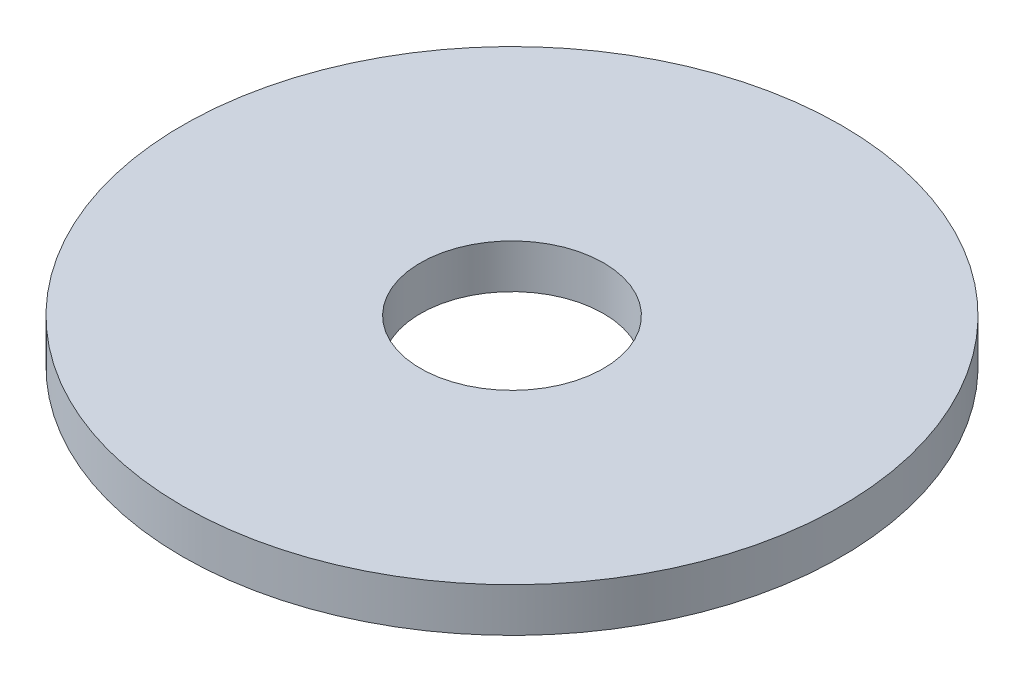
SolidWorks part; units mm, degrees
ref_plane "Front Plane" through (0, 0, 0) normal (0, 0, 1) x (1, 0, 0)
ref_plane "Top Plane" through (0, 0, 0) normal (0, 1, 0) x (1, 0, 0)
ref_plane "Right Plane" through (0, 0, 0) normal (1, 0, 0) x (0, 0, -1)
sketch "Sketch1" plane through (0, 0, 0) normal (0, 1, 0) x (1, 0, 0)
  circle A0 centre (0, 0) radius 1.9844
  circle A1 centre (0, 0) radius 7.1438
  dimension "D1" = 3.9688
  dimension "D2" = 14.2875
extrude "Boss-Extrude1" add sketch "Sketch1" along normal blind 0.9525
